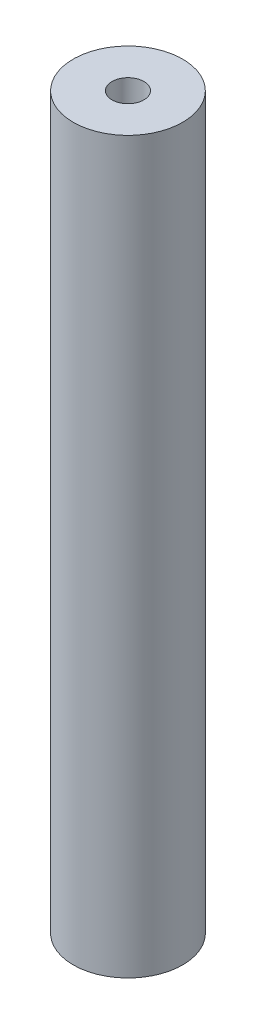
SolidWorks part; units mm, degrees
material "Brass"
ref_plane "Front Plane" through (0, 0, 0) normal (0, 0, 1) x (1, 0, 0)
ref_plane "Top Plane" through (0, 0, 0) normal (0, 1, 0) x (1, 0, 0)
ref_plane "Right Plane" through (0, 0, 0) normal (1, 0, 0) x (0, 0, -1)
sketch "Sketch1" plane through (0, 0, 0) normal (0, 1, 0) x (1, 0, 0)
  circle A0 centre (0, 0) radius 3
  dimension "D1" = 6
extrude "Boss-Extrude1" add sketch "Sketch1" along normal blind 40
sketch "Sketch2" plane through (0, 40, 0) normal (0, 1, 0) x (1, 0, 0)
  circle A0 centre (0, 0) radius 0.875
  dimension "D1" = 1.75
extrude "Cut-Extrude1" cut sketch "Sketch2" against normal through all
chamfer "Chamfer1" [suppressed] distance 1 angle 45
